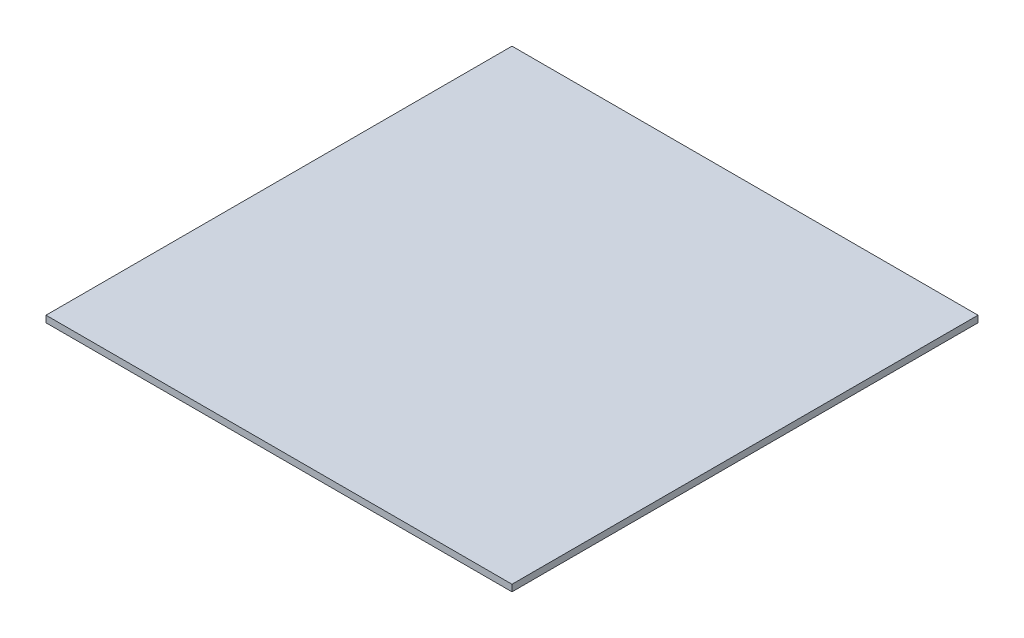
SolidWorks part; units mm, degrees
ref_plane "Front Plane" through (0, 0, 0) normal (0, 0, 1) x (1, 0, 0)
ref_plane "Top Plane" through (0, 0, 0) normal (0, 1, 0) x (1, 0, 0)
ref_plane "Right Plane" through (0, 0, 0) normal (1, 0, 0) x (0, 0, -1)
sketch "Sketch1" plane through (0, 0, 0) normal (0, 1, 0) x (1, 0, 0)
  line L1 (-50, -50) -> (50, -50)
  line L2 (-50, -50) -> (-50, 50)
  line L3 (-50, 50) -> (50, 50)
  line L4 (50, -50) -> (50, 50)
  line L5 (-50, -50) -> (50, 50) construction
  line L6 (-50, 50) -> (50, -50) construction
  point P0 (0, 0)
  dimension "D1" = 100
extrude "Boss-Extrude1" add sketch "Sketch1" along normal mid plane 1.42
